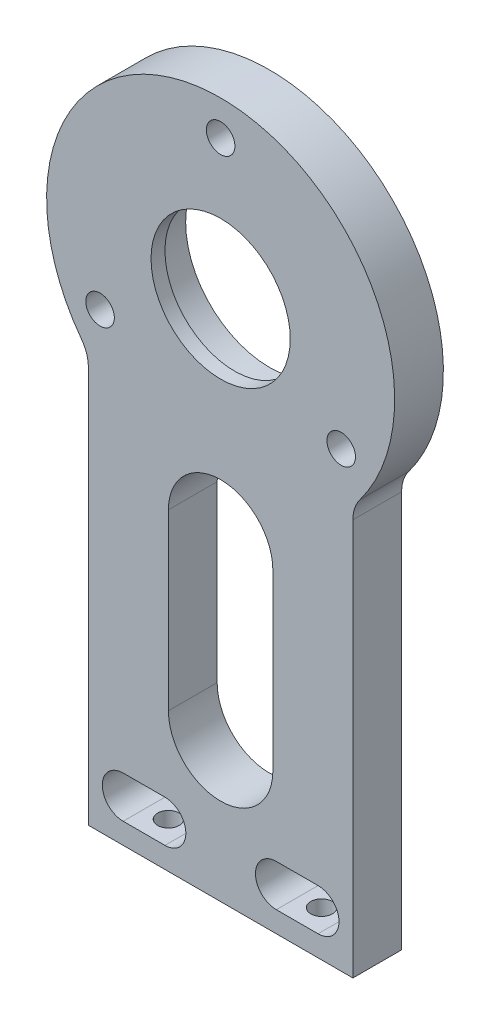
SolidWorks part; units mm, degrees
material "6061 合金"
ref_plane "前视基准面" through (0, 0, 0) normal (0, 0, 1) x (1, 0, 0)
ref_plane "上视基准面" through (0, 0, 0) normal (0, 1, 0) x (1, 0, 0)
ref_plane "右视基准面" through (0, 0, 0) normal (1, 0, 0) x (0, 0, -1)
sketch "草图1" plane through (0, 0, 0) normal (0, 0, 1) x (1, 0, 0)
  line L0 (0, 0) -> (0, 75) construction
  line L1 (-19, 0) -> (19, 0)
  line L2 (-19, 0) -> (-19, 7)
  line L3 (0, 45) -> (0, 20) construction
  line L4 (19, 7) -> (19, 0)
  line L5 (19, 57) -> (19, 7)
  line L6 (-19, 57) -> (-19, 7)
  line L7 (7.5, 45) -> (7.5, 20)
  line L8 (-7.5, 45) -> (-7.5, 20)
  line L9 (-8, 6) -> (-14, 6) construction
  line L10 (-8, 3) -> (-14, 3)
  line L11 (-8, 9) -> (-14, 9)
  line L12 (8, 6) -> (14, 6) construction
  line L13 (8, 3) -> (14, 3)
  line L14 (8, 9) -> (14, 9)
  circle A0 centre (0, 75) radius 10
  arc A1 (7.5, 45) -> (-7.5, 45) centre (0, 45) ccw
  arc A2 (19, 57) -> (20, 60) centre (24, 57) cw
  circle A3 centre (0, 75) radius 25
  arc A4 (-7.5, 20) -> (7.5, 20) centre (0, 20) ccw
  arc A5 (-19, 57) -> (-20, 60) centre (-24, 57) ccw
  circle A6 centre (0, 95) radius 2.05
  circle A7 centre (17.3205, 65) radius 2.05
  circle A8 centre (-17.3205, 65) radius 2.05
  arc A9 (-8, 3) -> (-8, 9) centre (-8, 6) ccw
  arc A10 (-14, 9) -> (-14, 3) centre (-14, 6) ccw
  arc A11 (8, 3) -> (8, 9) centre (8, 6) cw
  arc A12 (14, 9) -> (14, 3) centre (14, 6) cw
  point P9 (0, 32.5)
  point P30 (0, 75)
  point P31 (-11, 6)
  point P38 (11, 6)
  dimension "D4" = 50
  dimension "D5" = 20
  dimension "D6" = 30
  dimension "D7" = 7.5
  dimension "D8" = 4.1
  dimension "D2" = 20
  dimension "D3" = 75
  dimension "D10" = 20
  dimension "D12" = 5
  dimension "D13" = 3
  dimension "D14" = 6
  dimension "D15" = 8
  dimension "D16" = 6
  dimension "D1" = 38
  dimension "D9" = 40
  dimension "D11" = 3
extrude "凸台-拉伸1" add sketch "草图1" along normal mid plane 7
sketch "Sketch1" plane through (0, 0, -3.5) normal (0, 0, -1) x (-1, 0, 0)
  circle A2 centre (0, 75) radius 12.025
  dimension "D1" = 24.05
extrude "Cut-Extrude2" cut sketch "Sketch1" against normal blind 5
sketch "Sketch3" plane through (0, 0, -3.5) normal (0, 0, -1) x (-1, 0, 0)
  circle A0 centre (0, 95) radius 3.6
  circle A1 centre (17.3205, 65) radius 3.6
  circle A2 centre (-17.3205, 65) radius 3.6
  circle A3 centre (0, 75) radius 12.025 construction
  point P10 (0, 75)
  dimension "D1" = 7.2
  dimension "D2" = 3
extrude "Cut-Extrude4" cut sketch "Sketch3" against normal blind 4
sketch "Sketch4" plane through (0, 0, 0) normal (0, -1, 0) x (-1, 0, 0)
  line L0 (0, 0) -> (0, -24.1061) construction
  line L1 (-19, 0) -> (19, 0) construction
  line L3 (19, -3.5) -> (19, 3.5) construction
  line L4 (-19, -3.5) -> (-19, 3.5) construction
  circle A0 centre (11, 0) radius 1.55
  circle A1 centre (-11, 0) radius 1.55
  dimension "D1" = 3.1
  dimension "D2" = 8
extrude "Cut-Extrude5" cut sketch "Sketch4" against normal blind 5
sketch "Sketch6" [suppressed] plane through (0, 0, -3.5) normal (0, 0, -1) x (-1, 0, 0)
  line L0 (-19, 57) -> (-19, 0) construction
  line L1 (19, 0) -> (-19, 0)
  line L2 (19, 0) -> (19, 5)
  line L3 (19, 5) -> (-19, 5)
  line L4 (-19, 0) -> (-19, 5)
  line L5 (19, 57) -> (19, 0) construction
  line L6 (16, 5) -> (12, 5)
  line L7 (16, 5) -> (16, 55)
  line L8 (16, 55) -> (12, 55)
  line L9 (12, 5) -> (12, 55)
  line L10 (0, 0) -> (0, 140.1945) construction
  line L11 (-16, 55) -> (-12, 55)
  line L12 (-12, 5) -> (-12, 55)
  line L13 (-16, 5) -> (-12, 5)
  line L14 (-16, 5) -> (-16, 55)
  line M7 (-19, 57) -> (-19, 0)
  line M8 (-19, 0) -> (19, 0)
  line M9 (19, 0) -> (19, 57)
  dimension "D1" = 5
  dimension "D2" = 50
  dimension "D3" = 4
  dimension "D4" = 3
sketch "Sketch8" [suppressed] plane through (0, 0, 3.5) normal (0, 0, 1) x (1, 0, 0)
  line L0 (0, 75) -> (0, 115.5563) construction
  circle A0 centre (0, 75) radius 25
  circle A1 centre (0, 95) radius 2.05
  circle A2 centre (-17.3205, 65) radius 2.05
  circle A3 centre (17.3205, 65) radius 2.05
  circle A4 centre (0, 75) radius 12
  arc A5 (-5.0765, 50.5208) -> (5.0765, 50.5208) centre (0, 45) cw
  arc A6 (-13.7658, 95.8687) -> (-6.0766, 85.3477) centre (-16.0458, 86.1321) cw
  arc A7 (13.7658, 95.8687) -> (6.0766, 85.3477) centre (16.0458, 86.1321) ccw
  arc A8 (24.9557, 76.4872) -> (11.9997, 75.0886) centre (17.6635, 83.33) cw
  arc A9 (11.1899, 52.6441) -> (5.9231, 64.5637) centre (1.6178, 55.5379) ccw
  arc A10 (-11.1899, 52.6441) -> (-5.9231, 64.5637) centre (-1.6178, 55.5379) cw
  arc A11 (-24.9557, 76.4872) -> (-11.9997, 75.0886) centre (-17.6635, 83.33) ccw
  point P41 (0, 75)
  arc M2 (20, 60) -> (-20, 60) centre (0, 75) ccw
  circle M7 centre (-17.3205, 65) radius 2.05
  circle M8 centre (17.3205, 65) radius 2.05
  circle M9 centre (0, 95) radius 2.05
  dimension "D1" = 24
  dimension "D2" = 10
  dimension "D3" = 50
extrude "Boss-Extrude3" [suppressed] add sketch "Sketch8" along normal blind 7 contours A11 A0 A10 A4 M2 M7 | L0 A4 A7 A0 A1 | A9 A0 A8 A4 M2 M8 | A4 L0 A6 M9 M2
extrude "Boss-Extrude4" [suppressed] add sketch "Sketch6" along normal blind 10 contours L9 L3 L7 L8 | L14 L3 L12 L11 | L10 L3 M8 M7 | L10 L1 L3 M9
sketch "Sketch9" [suppressed] plane through (16, 0, 0) normal (1, 0, 0) x (0, 0, -1)
  line L2 (3.5, 55) -> (13.5, 55)
  line L3 (13.5, 55) -> (13.5, 5)
  line L5 (13.5, 5) -> (11.5, 5)
  line L6 (11.5, 5) -> (3.5, 55)
  dimension "D1" = 2
extrude "Cut-Extrude6" [suppressed] cut sketch "Sketch9" against normal through all
sketch "Sketch10" [suppressed] plane through (0, 0, 0) normal (0, -1, 0) x (1, 0, 0)
  line L0 (0, 0) -> (0, -46.2023) construction
  line L1 (-19, 3.5) -> (-19, -13.5) construction
  line L2 (19, -13.5) -> (-19, -13.5) construction
  circle A0 centre (-9, -8.5) radius 1.55
  circle A1 centre (9, -8.5) radius 1.55
  dimension "D1" = 3.1
  dimension "D2" = 10
  dimension "D3" = 5
extrude "Cut-Extrude7" [suppressed] cut sketch "Sketch10" against normal blind 10
fillet "Fillet4" [suppressed] radius 2
fillet "Fillet5" [suppressed] radius 2
fillet "Fillet7" [suppressed] radius 5
